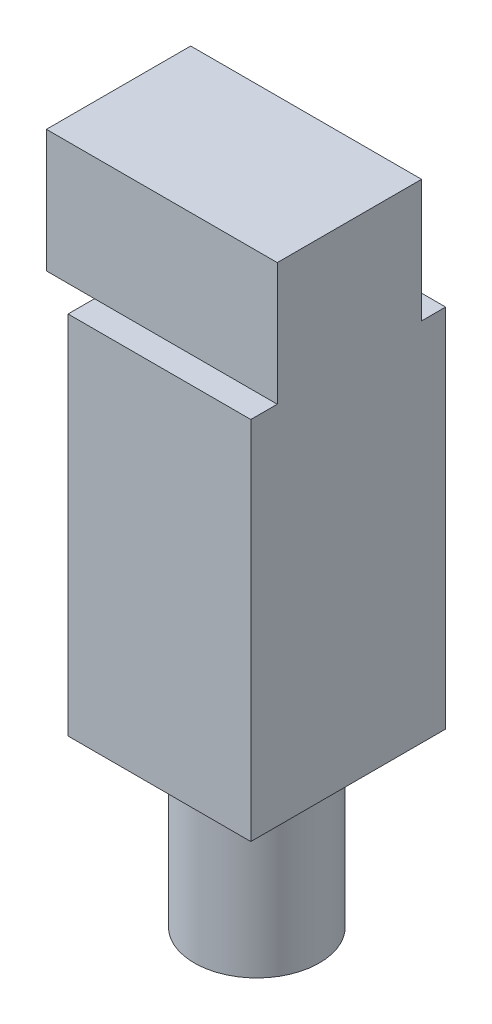
SolidWorks part; units mm, degrees
ref_plane "Front Plane" through (0, 0, 0) normal (0, 0, 1) x (1, 0, 0)
ref_plane "Top Plane" through (0, 0, 0) normal (0, 1, 0) x (1, 0, 0)
ref_plane "Right Plane" through (0, 0, 0) normal (1, 0, 0) x (0, 0, -1)
sketch "Sketch1" plane through (0, 0, 0) normal (1, 0, 0) x (0, 0, -1)
  line L1 (-20.25, -38) -> (20.25, -38)
  line L2 (-20.25, -38) -> (-20.25, 38)
  line L3 (-20.25, 38) -> (20.25, 38)
  line L4 (20.25, -38) -> (20.25, 38)
  line L5 (-20.25, -38) -> (20.25, 38) construction
  line L6 (-20.25, 38) -> (20.25, -38) construction
  point P0 (0, 0)
  dimension "D1" = 40.5
  dimension "D2" = 76
extrude "Boss-Extrude1" add sketch "Sketch1" along normal mid plane 38
sketch "Sketch2" plane through (0, -38, 0) normal (0, -1, 0) x (1, 0, 0)
  circle A0 centre (0, 0) radius 13
  dimension "D1" = 26
extrude "Boss-Extrude2" add sketch "Sketch2" along normal blind 35
ref_plane "Plane1" through (0, 0, -15.25) normal (0, 0, -1) x (-1, 0, 0)
sketch "Sketch3" plane through (0, 0, -15.25) normal (0, 0, -1) x (-1, 0, 0)
  line L0 (-19, 38) -> (19, 38) construction
  line L1 (-19, 38) -> (29, 38)
  line L2 (-19, 38) -> (-19, 63.5)
  line L3 (-19, 63.5) -> (29, 63.5)
  line L4 (29, 38) -> (29, 63.5)
  line L5 (-19, -38) -> (-19, 38) construction
  dimension "D1" = 25.5
  dimension "D2" = 48
extrude "Boss-Extrude3" add sketch "Sketch3" against normal blind 30
sketch "Sketch4" plane through (-29, 0, 0) normal (-1, 0, 0) x (0, 0, 1)
  line L0 (14.75, 63.5) -> (-15.25, 63.5) construction
  circle A0 centre (0, 53.5) radius 4.5
  dimension "D1" = 9
  dimension "D2" = 10
extrude "Boss-Extrude4" add sketch "Sketch4" along normal blind 5
